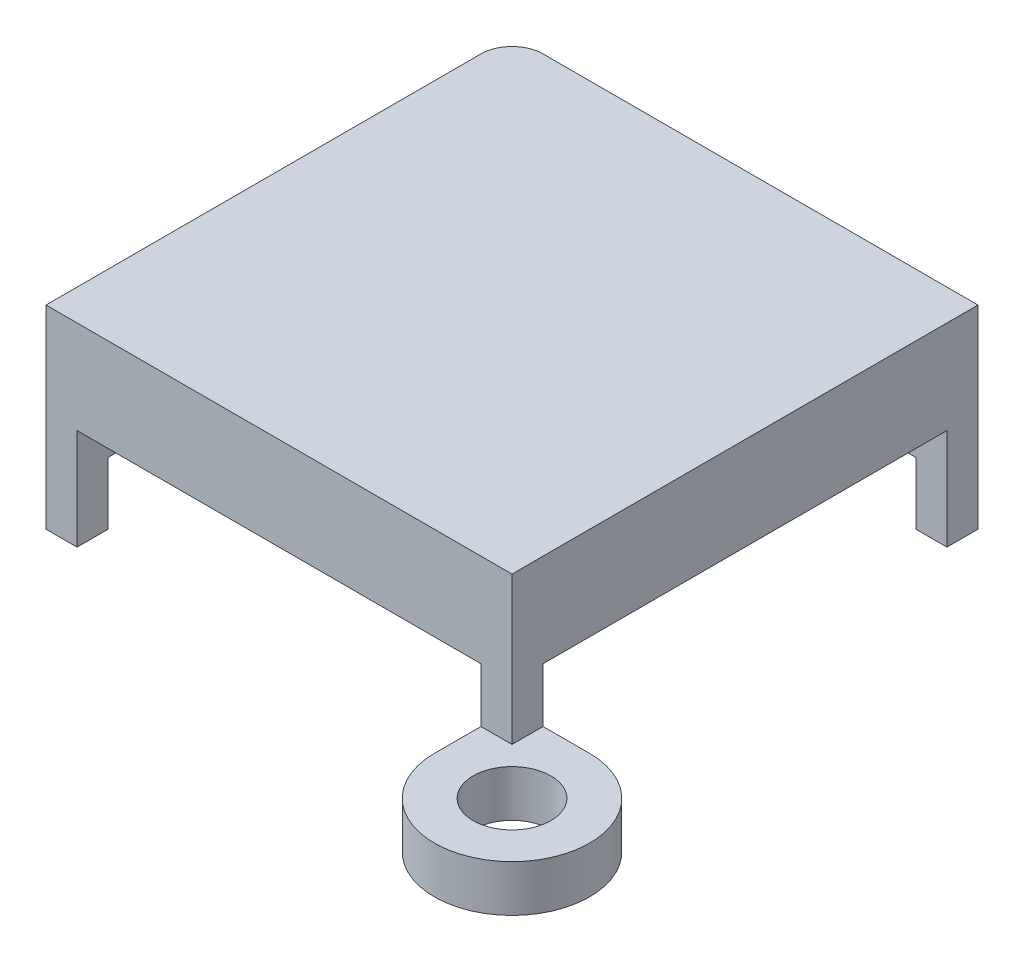
SolidWorks part; units mm, degrees
ref_plane "前视基准面" through (0, 0, 0) normal (0, 0, 1) x (1, 0, 0)
ref_plane "上视基准面" through (0, 0, 0) normal (0, 1, 0) x (1, 0, 0)
ref_plane "右视基准面" through (0, 0, 0) normal (1, 0, 0) x (0, 0, -1)
sketch "草图1" plane through (0, 0, 0) normal (0, 1, 0) x (1, 0, 0)
  line L1 (-3, 3) -> (3, 3)
  line L2 (-3, 3) -> (-3, -3)
  line L3 (-3, -3) -> (3, -3)
  line L4 (3, 3) -> (3, -3)
  line L5 (-3, 3) -> (3, -3) construction
  line L6 (-3, -3) -> (3, 3) construction
  point P0 (0, 0)
  dimension "D1" = 6
  dimension "D2" = 6
extrude "凸台-拉伸1" add sketch "草图1" along normal blind 0.5
sketch "草图2" plane through (0, 0, 0) normal (0, -1, 0) x (1, 0, 0)
  line L0 (-2.6, 2.6) -> (-2.6, -2.6)
  line L1 (-2.6, -2.6) -> (2.6, -2.6)
  line L2 (2.6, -2.6) -> (2.6, 2.6)
  line L3 (2.6, 2.6) -> (-2.6, 2.6)
  line L4 (3, -3) -> (3, 3)
  line L5 (3, 3) -> (-3, 3)
  line L6 (-3, 3) -> (-3, -3)
  line L7 (-3, -3) -> (3, -3)
  line L8 (3, -3) -> (3, 3)
  line L9 (3, 3) -> (-3, 3)
  line L10 (-3, 3) -> (-3, -3)
  line L11 (-3, -3) -> (3, -3)
  dimension "D1" = 0
  dimension "D2" = 0.4
extrude "凸台-拉伸2" add sketch "草图2" along normal blind 2
sketch "草图3" plane through (-3, 0, 0) normal (-1, 0, 0) x (0, 0, 1)
  line L1 (-2.6, -0.2) -> (2.6, -0.2)
  line L2 (-2.6, -0.2) -> (-2.6, -2)
  line L3 (-2.6, -2) -> (2.6, -2)
  line L4 (2.6, -0.2) -> (2.6, -2)
  line L5 (3, -2) -> (-3, -2) construction
  line L6 (-3, 0.5) -> (-3, -2) construction
  dimension "D1" = 5.2
  dimension "D2" = 0.4
  dimension "D3" = 1.8
extrude "切除-拉伸1" cut sketch "草图3" against normal through all
sketch "草图4" plane through (0, 0, -3) normal (0, 0, -1) x (-1, 0, 0)
  line L0 (3, -2) -> (-3, -2) construction
  line L1 (-2.6, -0.2) -> (2.6, -0.2)
  line L2 (-2.6, -0.2) -> (-2.6, -2)
  line L3 (-2.6, -2) -> (2.6, -2)
  line L4 (2.6, -0.2) -> (2.6, -2)
  line L5 (-3, 0.5) -> (-3, -2) construction
  dimension "D1" = 5.2
  dimension "D2" = 0.4
  dimension "D3" = 1.8
extrude "切除-拉伸2" cut sketch "草图4" against normal through all
sketch "草图5" plane through (0, -2, 0) normal (0, -1, 0) x (1, 0, 0)
  line L1 (2.6, 2.6) -> (4.6, 2.6)
  line L2 (2.6, 2.6) -> (2.6, 4.6)
  line L3 (2.6, 4.6) -> (4.6, 4.6)
  line L4 (4.6, 2.6) -> (4.6, 4.6)
  circle A0 centre (3.6, 3.6) radius 1
  circle A1 centre (3.6, 3.6) radius 0.5
  line M5 (2.6, 3) -> (2.6, 2.6)
  line M7 (3, 2.6) -> (3, 3)
  line M8 (3, 3) -> (2.6, 3)
  line M11 (2.6, 2.6) -> (3, 2.6)
  dimension "D3" = 2
  dimension "D4" = 1
  dimension "D1" = 2
  dimension "D2" = 2
extrude "凸台-拉伸3" add sketch "草图5" against normal blind 0.6 contours A0 A1 M8 M7 | A0 L2 M8 | A0 L1 M7 | A0 M8 M5 M11 M7 | A0 M8 M7
sketch "草图6" plane through (0, -0.2, 0) normal (0, -1, 0) x (1, 0, 0)
  line L4 (-2.6, 2.6) -> (2.6, 2.6)
  line L5 (2.6, 2.6) -> (2.6, 3)
  line L6 (2.6, 3) -> (-2.6, 3)
  line L7 (-2.6, 3) -> (-2.6, 2.6)
  line L8 (-2.6, 2.6) -> (2.6, 2.6)
  line L9 (2.6, 2.6) -> (2.6, 3)
  line L10 (2.6, 3) -> (-2.6, 3)
  line L11 (-2.6, 3) -> (-2.6, 2.6)
  dimension "D1" = 0
extrude "凸台-拉伸4" add sketch "草图6" along normal blind 0.5
sketch "草图7" plane through (0, -0.2, 0) normal (0, -1, 0) x (1, 0, 0)
  line L4 (2.6, 2.6) -> (2.6, -2.6)
  line L5 (2.6, -2.6) -> (3, -2.6)
  line L6 (3, -2.6) -> (3, 2.6)
  line L7 (3, 2.6) -> (2.6, 2.6)
  line L8 (2.6, 2.6) -> (2.6, -2.6)
  line L9 (2.6, -2.6) -> (3, -2.6)
  line L10 (3, -2.6) -> (3, 2.6)
  line L11 (3, 2.6) -> (2.6, 2.6)
  dimension "D1" = 0
extrude "凸台-拉伸5" add sketch "草图7" along normal blind 0.5
sketch "草图8" plane through (0, -0.2, 0) normal (0, -1, 0) x (1, 0, 0)
  line L4 (-2.6, -2.6) -> (-2.6, 2.6)
  line L5 (-2.6, 2.6) -> (-3, 2.6)
  line L6 (-3, 2.6) -> (-3, -2.6)
  line L7 (-3, -2.6) -> (-2.6, -2.6)
  line L8 (-2.6, -2.6) -> (-2.6, 2.6)
  line L9 (-2.6, 2.6) -> (-3, 2.6)
  line L10 (-3, 2.6) -> (-3, -2.6)
  line L11 (-3, -2.6) -> (-2.6, -2.6)
  dimension "D1" = 0
extrude "凸台-拉伸6" add sketch "草图8" along normal blind 1
sketch "草图9" plane through (0, -0.2, 0) normal (0, -1, 0) x (1, 0, 0)
  line L4 (2.6, -2.6) -> (-2.6, -2.6)
  line L5 (-2.6, -2.6) -> (-2.6, -3)
  line L6 (-2.6, -3) -> (2.6, -3)
  line L7 (2.6, -3) -> (2.6, -2.6)
  line L8 (2.6, -2.6) -> (-2.6, -2.6)
  line L9 (-2.6, -2.6) -> (-2.6, -3)
  line L10 (-2.6, -3) -> (2.6, -3)
  line L11 (2.6, -3) -> (2.6, -2.6)
  dimension "D1" = 0
extrude "凸台-拉伸7" add sketch "草图9" along normal blind 1
sketch "草图10" plane through (0, -1.2, 0) normal (0, -1, 0) x (1, 0, 0)
  line L0 (-3, 2.6) -> (-3, -2.6) construction
  line L1 (-3, 0.5) -> (-2.6, 0.5)
  line L2 (-3, 0.5) -> (-3, -0.5)
  line L3 (-3, -0.5) -> (-2.6, -0.5)
  line L4 (-2.6, 0.5) -> (-2.6, -0.5)
  line L5 (-2.6, 2.6) -> (-2.6, -2.6) construction
  line L6 (2.6, -2.6) -> (-2.6, -2.6) construction
  line L7 (-0.5, -2.6) -> (0.5, -2.6)
  line L8 (-0.5, -2.6) -> (-0.5, -3)
  line L9 (-0.5, -3) -> (0.5, -3)
  line L10 (0.5, -2.6) -> (0.5, -3)
  line L11 (-2.6, -3) -> (2.6, -3) construction
  point P16 (-3, 0)
  point P17 (0, -3)
  dimension "D1" = 1
  dimension "D2" = 1
extrude "切除-拉伸3" cut sketch "草图10" against normal blind 0.5
fillet "圆角2" radius 0.4 1 edges at (-3, -0.75, -3)
